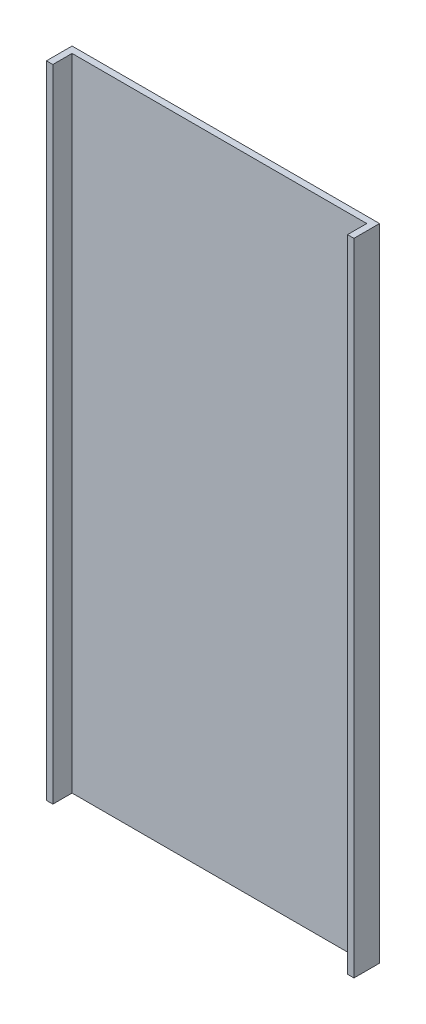
SolidWorks part; units mm, degrees
ref_plane "Ebene vorne" through (0, 0, 0) normal (0, 0, 1) x (1, 0, 0)
ref_plane "Ebene oben" through (0, 0, 0) normal (0, 1, 0) x (1, 0, 0)
ref_plane "Ebene rechts" through (0, 0, 0) normal (1, 0, 0) x (0, 0, -1)
sketch "Skizze1" plane through (0, 0, 0) normal (0, 1, 0) x (1, 0, 0)
  line L0 (0, 0) -> (10, 0)
  line L5 (10, 0) -> (10, 30)
  line L6 (10, 30) -> (470, 30)
  line L7 (470, 30) -> (470, 0)
  line L8 (470, 0) -> (480, 0)
  line L9 (480, 0) -> (480, 40)
  line L10 (480, 40) -> (0, 40)
  line L11 (0, 40) -> (0, 0)
  dimension "D1" = 480
  dimension "D2" = 10
  dimension "D3" = 10
  dimension "D4" = 40
  dimension "D5" = 30
extrude "Aufsatz-Linear austragen1" add sketch "Skizze1" along normal blind 1000
